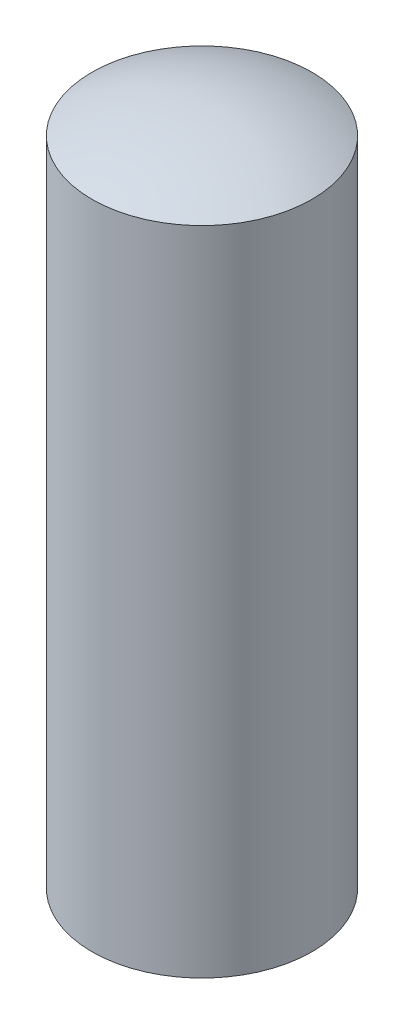
SolidWorks part; units mm, degrees
material "Plain Carbon Steel"
ref_plane "Front Plane" through (0, 0, 0) normal (0, 0, 1) x (1, 0, 0)
ref_plane "Top Plane" through (0, 0, 0) normal (0, 1, 0) x (1, 0, 0)
ref_plane "Right Plane" through (0, 0, 0) normal (1, 0, 0) x (0, 0, -1)
other "Configuration Table"
sketch "Sketch1" plane through (0, 0, 0) normal (0, 0, 1) x (1, 0, 0)
  line L0 (0, 5) -> (0, -37) construction
  line L1 (5, -1.2) -> (-5, -1.2) construction
  line L2 (5, -1.2) -> (5, -30.8)
  line L3 (5, -30.8) -> (-5, -30.8) construction
  line L4 (5, -32) -> (-5, -32) construction
  line L5 (0, -32) -> (0, 0)
  arc A0 (0, 0) -> (5, -1.2) centre (0, -11.0167) cw
  arc A1 (-5, -1.2) -> (0, 0) centre (0, -11.0167) cw construction
  arc A2 (5, -30.8) -> (0, -32) centre (0, -20.9833) cw
  arc A3 (0, -32) -> (-5, -30.8) centre (0, -20.9833) cw construction
  dimension "D1" = 1.2
  dimension "D2" = 10
  dimension "D3" = 1.2
  dimension "D4" = 5
  dimension "D5" = 5
  dimension "Length" = 32
revolve "Revolve1" add sketch "Sketch1" angle 360 about L0
